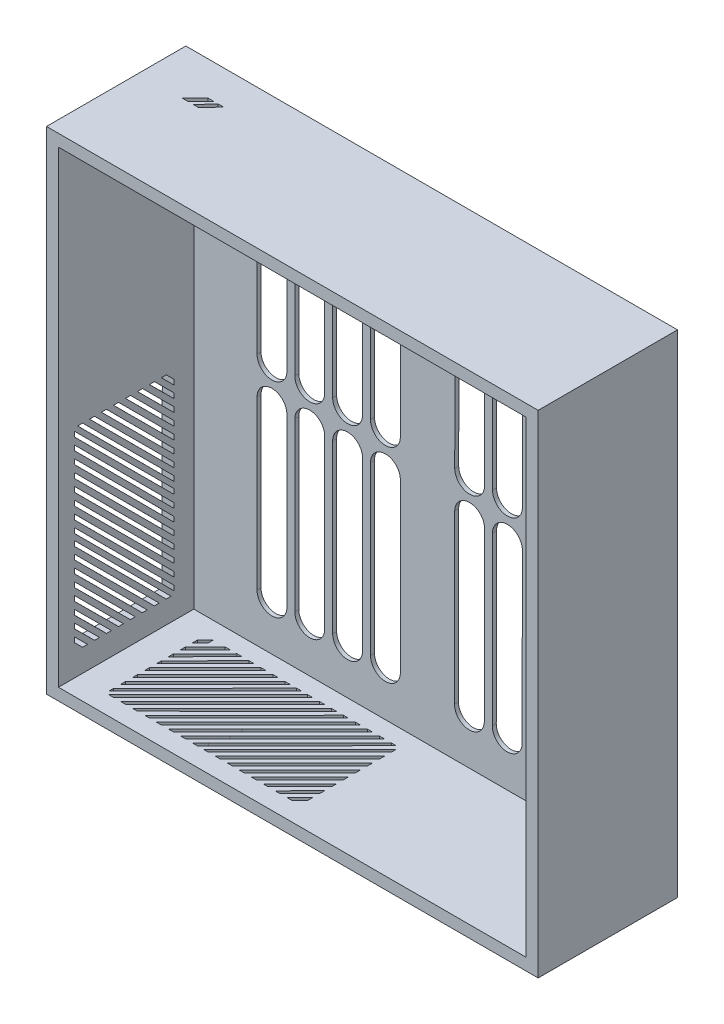
SolidWorks part; units mm, degrees
ref_plane "Plano frontal" through (0, 0, 0) normal (0, 0, 1) x (1, 0, 0)
ref_plane "Plano superior" through (0, 0, 0) normal (0, 1, 0) x (1, 0, 0)
ref_plane "Plano direito" through (0, 0, 0) normal (1, 0, 0) x (0, 0, -1)
sketch "Esboço1" plane through (0, 0, 0) normal (0, 0, 1) x (1, 0, 0)
  line L1 (-16.5696, 236.8339) -> (230.4304, 236.8339)
  line L2 (-16.5696, 236.8339) -> (-16.5696, -10.1661)
  line L3 (-16.5696, -10.1661) -> (230.4304, -10.1661)
  line L4 (230.4304, 236.8339) -> (230.4304, -10.1661)
  dimension "D1" = 247
  dimension "D2" = 247
extrude "Ressalto-extrusão1" add sketch "Esboço1" along normal blind 70 contours L2 L1 L4 L3
sketch "Esboço2" plane through (0, 0, 70) normal (0, 0, 1) x (1, 0, 0)
  line L0 (230.4304, 236.8339) -> (230.4304, -10.1661) construction
  line L1 (-10.5696, 230.8339) -> (224.4304, 230.8339)
  line L2 (-10.5696, 230.8339) -> (-10.5696, -4.1661)
  line L3 (-10.5696, -4.1661) -> (224.4304, -4.1661)
  line L4 (224.4304, 230.8339) -> (224.4304, -4.1661)
  line L5 (-16.5696, 236.8339) -> (230.4304, 236.8339) construction
  line L6 (-16.5696, 236.8339) -> (-16.5696, -10.1661) construction
  line L7 (-16.5696, -10.1661) -> (230.4304, -10.1661) construction
  dimension "D1" = 6
  dimension "D2" = 6
  dimension "D3" = 6
  dimension "D4" = 6
extrude "Corte-extrusão1" cut sketch "Esboço2" against normal blind 68
sketch "Esboço6" plane through (0, 0, 2) normal (0, 0, 1) x (1, 0, 0)
  line L0 (21.1965, 206.6676) -> (21.1965, 122.654)
  line L1 (36.1965, 206.6676) -> (36.1965, 122.654)
  line L2 (40.1965, 206.6676) -> (40.1965, 122.654)
  line L3 (55.1965, 122.654) -> (55.1965, 206.6676)
  line L4 (59.1965, 206.6676) -> (59.1965, 122.654)
  line L5 (78.1965, 206.6676) -> (78.1965, 122.654)
  line L6 (74.1965, 122.654) -> (74.1965, 206.6676)
  line L7 (93.1965, 122.654) -> (93.1965, 206.6676)
  line L9 (93.1965, 104.0138) -> (93.1965, 20.0002)
  line L17 (-10.5696, 113.3339) -> (224.4304, 113.3339) construction
  line L18 (-10.5696, 230.8339) -> (-10.5696, -4.1661) construction
  line L19 (224.4304, -4.1661) -> (224.4304, 230.8339) construction
  line L20 (74.1965, 104.0138) -> (74.1965, 20.0002)
  line L21 (78.1965, 20.0002) -> (78.1965, 104.0138)
  line L22 (59.1965, 20.0002) -> (59.1965, 104.0138)
  line L23 (55.1965, 104.0138) -> (55.1965, 20.0002)
  line L24 (40.1965, 20.0002) -> (40.1965, 104.0138)
  line L25 (36.1965, 20.0002) -> (36.1965, 104.0138)
  line L26 (21.1965, 20.0002) -> (21.1965, 104.0138)
  line L27 (192.3761, 19.8832) -> (192.4909, 103.8967)
  line L28 (106.9201, 215.6583) -> (106.9304, 230.8339) construction
  line L29 (224.4304, 230.8339) -> (-10.5696, 230.8339) construction
  line L30 (177.3761, 19.9037) -> (177.4909, 103.9172)
  line L31 (173.3761, 19.9092) -> (173.491, 103.9227)
  line L32 (158.491, 103.9432) -> (158.3762, 19.9297)
  line L33 (154.3762, 19.9351) -> (154.491, 103.9487)
  line L34 (135.3762, 19.9611) -> (135.491, 103.9746)
  line L35 (139.491, 103.9692) -> (139.3762, 19.9556)
  line L36 (120.491, 103.9951) -> (120.3762, 19.9816)
  line L37 (120.5165, 122.6353) -> (120.6313, 206.6489)
  line L38 (139.5165, 122.6094) -> (139.6313, 206.6229)
  line L39 (135.6313, 206.6284) -> (135.5165, 122.6148)
  line L40 (154.6313, 206.6024) -> (154.5164, 122.5889)
  line L41 (158.5164, 122.5834) -> (158.6312, 206.5969)
  line L42 (173.6312, 206.5764) -> (173.5164, 122.5629)
  line L43 (177.6312, 206.571) -> (177.5164, 122.5574)
  line L44 (192.6312, 206.5505) -> (192.5164, 122.5369)
  line L45 (-10.5696, -4.1661) -> (224.4304, -4.1661) construction
  arc A112 (36.1965, 206.6676) -> (21.1965, 206.6676) centre (28.6965, 206.6676) ccw
  arc A113 (21.1965, 122.654) -> (36.1965, 122.654) centre (28.6965, 122.654) ccw
  arc A114 (40.1965, 206.6676) -> (55.1965, 206.6676) centre (47.6965, 206.6676) cw
  arc A115 (40.1965, 122.654) -> (55.1965, 122.654) centre (47.6965, 122.654) ccw
  arc A116 (59.1965, 206.6676) -> (74.1965, 206.6676) centre (66.6965, 206.6676) cw
  arc A117 (59.1965, 122.654) -> (74.1965, 122.654) centre (66.6965, 122.654) ccw
  arc A118 (78.1965, 206.6676) -> (93.1965, 206.6676) centre (85.6965, 206.6676) cw
  arc A119 (78.1965, 122.654) -> (93.1965, 122.654) centre (85.6965, 122.654) ccw
  arc A128 (78.1965, 104.0138) -> (93.1965, 104.0138) centre (85.6965, 104.0138) cw
  arc A129 (78.1965, 20.0002) -> (93.1965, 20.0002) centre (85.6965, 20.0002) ccw
  arc A130 (59.1965, 104.0138) -> (74.1965, 104.0138) centre (66.6965, 104.0138) cw
  arc A131 (59.1965, 20.0002) -> (74.1965, 20.0002) centre (66.6965, 20.0002) ccw
  arc A132 (40.1965, 104.0138) -> (55.1965, 104.0138) centre (47.6965, 104.0138) cw
  arc A133 (40.1965, 20.0002) -> (55.1965, 20.0002) centre (47.6965, 20.0002) ccw
  arc A134 (21.1965, 104.0138) -> (36.1965, 104.0138) centre (28.6965, 104.0138) cw
  arc A135 (36.1965, 20.0002) -> (21.1965, 20.0002) centre (28.6965, 20.0002) cw
  arc A136 (177.3761, 19.9037) -> (192.3761, 19.8832) centre (184.8761, 19.8935) ccw
  arc A137 (192.4909, 103.8967) -> (177.4909, 103.9172) centre (184.9909, 103.907) ccw
  arc A138 (173.3761, 19.9092) -> (158.3762, 19.9297) centre (165.8762, 19.9194) cw
  arc A139 (173.491, 103.9227) -> (158.491, 103.9432) centre (165.991, 103.933) ccw
  arc A140 (154.3762, 19.9351) -> (139.3762, 19.9556) centre (146.8762, 19.9454) cw
  arc A141 (154.491, 103.9487) -> (139.491, 103.9692) centre (146.991, 103.9589) ccw
  arc A142 (135.3762, 19.9611) -> (120.3762, 19.9816) centre (127.8762, 19.9713) cw
  arc A143 (135.491, 103.9746) -> (120.491, 103.9951) centre (127.991, 103.9849) ccw
  arc A144 (135.5165, 122.6148) -> (120.5165, 122.6353) centre (128.0165, 122.6251) cw
  arc A145 (135.6313, 206.6284) -> (120.6313, 206.6489) centre (128.1313, 206.6386) ccw
  arc A146 (154.5164, 122.5889) -> (139.5165, 122.6094) centre (147.0165, 122.5991) cw
  arc A147 (154.6313, 206.6024) -> (139.6313, 206.6229) centre (147.1313, 206.6127) ccw
  arc A148 (173.5164, 122.5629) -> (158.5164, 122.5834) centre (166.0164, 122.5731) cw
  arc A149 (173.6312, 206.5764) -> (158.6312, 206.5969) centre (166.1312, 206.5867) ccw
  arc A150 (192.5164, 122.5369) -> (177.5164, 122.5574) centre (185.0164, 122.5472) cw
  arc A151 (177.6312, 206.571) -> (192.6312, 206.5505) centre (185.1312, 206.5607) cw
  dimension "D1" = 19
  dimension "D2" = 19
  dimension "D3" = 19
  dimension "D4" = 19
  dimension "D14" = 7.5
  dimension "D15" = 7.5
  dimension "D16" = 7.5
  dimension "D17" = 7.5
  dimension "D5" = 19
  dimension "D6" = 19
  dimension "D7" = 19
  dimension "D8" = 19
  dimension "D9" = 18.9745
  dimension "D10" = 19
  dimension "D11" = 19
  dimension "D12" = 19
  dimension "D13" = 21.2174
extrude "Corte-extrusão2" cut sketch "Esboço6" against normal through all
sketch "Esboço8" plane through (-16.5696, 0, 0) normal (-1, 0, 0) x (0, 0, 1)
  line L7 (11.8956, 54.7334) -> (61.8956, 54.7334) construction
  line L11 (61.8956, 7.1713) -> (61.8956, 104.6924) construction
  line L12 (61.8956, 104.6924) -> (11.8956, 104.6924) construction
  line L13 (11.8956, 104.6924) -> (11.8956, 7.1713) construction
  line L169 (11.8956, 100.7307) -> (15.8573, 104.6924)
  line L170 (11.8956, 98.2307) -> (18.3573, 104.6924)
  line L171 (18.3573, 104.6924) -> (15.8573, 104.6924)
  line L172 (11.8956, 98.2307) -> (11.8956, 100.7307)
  line L173 (11.8523, 94.7756) -> (21.7577, 104.6924)
  line L174 (11.8538, 92.2756) -> (24.3573, 104.6924)
  line L175 (24.3573, 104.6924) -> (21.7577, 104.6924)
  line L176 (11.8538, 92.2756) -> (11.8523, 94.7756)
  line L177 (11.8619, 88.7609) -> (27.7906, 104.6924)
  line L178 (11.8622, 86.2609) -> (30.3573, 104.6924)
  line L179 (30.3573, 104.6924) -> (27.7906, 104.6924)
  line L180 (11.8622, 86.2609) -> (11.8619, 88.7609)
  line L181 (11.8641, 82.7649) -> (33.7943, 104.6924)
  line L182 (11.8639, 80.2649) -> (36.3573, 104.6924)
  line L183 (36.3573, 104.6924) -> (33.7943, 104.6924)
  line L184 (11.8639, 80.2649) -> (11.8641, 82.7649)
  line L185 (11.8656, 76.7627) -> (39.8121, 104.6924)
  line L186 (11.8648, 74.2627) -> (42.3573, 104.6924)
  line L187 (42.3573, 104.6924) -> (39.8121, 104.6924)
  line L188 (11.8648, 74.2627) -> (11.8656, 76.7627)
  line L189 (11.9387, 70.7309) -> (45.8573, 104.6924)
  line L190 (11.9387, 68.2309) -> (48.4001, 104.6924)
  line L191 (48.4001, 104.6924) -> (45.8573, 104.6924)
  line L192 (11.9387, 68.2309) -> (11.9387, 70.7309)
  line L193 (11.8959, 64.7311) -> (51.9039, 104.6924)
  line L194 (11.8959, 62.2311) -> (54.4071, 104.6924)
  line L195 (54.4071, 104.6924) -> (51.9039, 104.6924)
  line L196 (11.8959, 62.2311) -> (11.8959, 64.7311)
  line L197 (11.8715, 58.7626) -> (57.8573, 104.6924)
  line L198 (11.87, 56.2626) -> (60.3573, 104.6924)
  line L199 (60.3573, 104.6924) -> (57.8573, 104.6924)
  line L200 (11.87, 56.2626) -> (11.8715, 58.7626)
  line L201 (61.4363, 104.2154) -> (11.8956, 54.7334) construction
  line L202 (61.912, 103.1358) -> (61.909, 100.6358)
  line L203 (13.4247, 54.706) -> (61.912, 103.1358)
  line L204 (15.9247, 54.7033) -> (61.909, 100.6358)
  line L205 (61.9049, 97.1857) -> (61.902, 94.6825)
  line L206 (61.8978, 91.1787) -> (61.8948, 88.6358)
  line L207 (61.8906, 85.1358) -> (61.8876, 82.5906)
  line L208 (61.8835, 79.1358) -> (61.8805, 76.5729)
  line L209 (61.8764, 73.1358) -> (61.8734, 70.5692)
  line L210 (61.8693, 67.1359) -> (61.8662, 64.5363)
  line L211 (61.8622, 61.1359) -> (61.8592, 58.6359)
  line L212 (60.3408, 57.1191) -> (61.8592, 58.6359)
  line L213 (57.8332, 57.1218) -> (61.8622, 61.1359)
  line L214 (59.4625, 54.7334) -> (11.8956, 54.7334) construction
  line L215 (51.9262, 57.1282) -> (61.8693, 67.1359)
  line L216 (11.9387, 47.12) -> (21.9593, 57.1605)
  line L217 (11.936, 44.62) -> (24.4519, 57.1578)
  line L218 (11.936, 44.62) -> (11.9387, 47.12)
  line L219 (11.9322, 41.1181) -> (27.8522, 57.1541)
  line L220 (11.9295, 38.6181) -> (30.391, 57.1514)
  line L221 (11.9295, 38.6181) -> (11.9322, 41.1181)
  line L222 (11.9258, 35.1164) -> (33.8937, 57.1476)
  line L223 (11.9231, 32.6463) -> (36.4316, 57.1449)
  line L224 (11.9231, 32.6463) -> (11.9258, 35.1164)
  line L225 (11.9193, 29.1152) -> (39.8992, 57.1411)
  line L226 (11.9166, 26.6516) -> (42.4294, 57.1384)
  line L227 (11.9166, 26.6516) -> (11.9193, 29.1152)
  line L228 (11.9128, 23.1198) -> (45.8987, 57.1347)
  line L229 (11.9102, 20.6616) -> (48.4211, 57.1319)
  line L230 (11.9102, 20.6616) -> (11.9128, 23.1198)
  line L231 (11.9064, 17.1283) -> (51.9262, 57.1282)
  line L232 (11.9037, 14.6719) -> (54.4408, 57.1254)
  line L233 (11.9037, 14.6719) -> (11.9064, 17.1283)
  line L234 (11.897, 11.1632) -> (57.8332, 57.1218)
  line L235 (11.8973, 8.7278) -> (60.3408, 57.1191)
  line L236 (11.8973, 8.7278) -> (11.897, 11.1632)
  line L237 (59.0348, 54.2596) -> (11.8956, 7.1713) construction
  line L238 (13.4521, 7.1713) -> (15.8875, 7.1684)
  line L239 (61.8956, 55.5626) -> (61.8956, 53.055)
  line L240 (13.4521, 7.1713) -> (61.8956, 55.5626)
  line L241 (15.8875, 7.1684) -> (61.8956, 53.055)
  line L242 (19.3962, 7.1713) -> (21.8526, 7.1713)
  line L243 (61.8956, 49.6626) -> (61.8956, 47.1479)
  line L244 (19.3962, 7.1713) -> (61.8956, 49.6626)
  line L245 (21.8526, 7.1713) -> (61.8956, 47.1479)
  line L246 (25.3859, 7.1713) -> (27.8441, 7.1713)
  line L247 (61.8956, 43.6429) -> (61.8956, 41.1204)
  line L248 (25.3859, 7.1713) -> (61.8956, 43.6429)
  line L249 (27.8441, 7.1713) -> (61.8956, 41.1204)
  line L250 (31.3759, 7.1713) -> (33.8396, 7.1713)
  line L251 (61.8956, 37.6512) -> (61.8956, 35.121)
  line L252 (31.3759, 7.1713) -> (61.8956, 37.6512)
  line L253 (33.8396, 7.1713) -> (61.8956, 35.121)
  line L254 (37.3706, 7.1713) -> (39.8407, 7.1713)
  line L255 (61.8956, 31.6534) -> (61.8956, 29.1154)
  line L256 (37.3706, 7.1713) -> (61.8956, 31.6534)
  line L257 (39.8407, 7.1713) -> (61.8956, 29.1154)
  line L258 (43.3424, 7.1713) -> (45.8424, 7.1713)
  line L259 (61.8956, 25.6127) -> (61.8956, 23.074)
  line L260 (43.3424, 7.1713) -> (61.8956, 25.6127)
  line L261 (45.8424, 7.1713) -> (61.8956, 23.074)
  line L262 (49.3443, 7.1713) -> (51.8443, 7.1713)
  line L263 (61.8956, 19.6736) -> (61.8956, 17.181)
  line L264 (49.3443, 7.1713) -> (61.8956, 19.6736)
  line L265 (51.8443, 7.1713) -> (61.8956, 17.181)
  line L266 (55.3872, 7.1713) -> (57.8872, 7.1713)
  line L267 (61.906, 13.6631) -> (61.8956, 11.1631)
  line L268 (55.3872, 7.1713) -> (61.906, 13.6631)
  line L269 (57.8872, 7.1713) -> (61.8956, 11.1631)
  line L270 (13.4247, 54.706) -> (11.8956, 53.1787)
  line L271 (11.8956, 53.1787) -> (11.8956, 50.6787)
  line L272 (11.8956, 50.6787) -> (15.9247, 54.7033)
  line L273 (21.9593, 57.1605) -> (61.9049, 97.1857)
  line L274 (24.4519, 57.1578) -> (61.902, 94.6825)
  line L275 (27.8522, 57.1541) -> (61.8978, 91.1787)
  line L276 (30.391, 57.1514) -> (61.8948, 88.6358)
  line L277 (13.4521, 7.1713) -> (61.8956, 7.1713) construction
  line L278 (54.4408, 57.1254) -> (61.8662, 64.5363)
  line L279 (45.8987, 57.1347) -> (61.8764, 73.1358)
  line L280 (48.4211, 57.1319) -> (61.8734, 70.5692)
  line L281 (39.8992, 57.1411) -> (61.8835, 79.1358)
  line L282 (42.4294, 57.1384) -> (61.8805, 76.5729)
  line L283 (33.8937, 57.1476) -> (61.8906, 85.1358)
  line L284 (36.4316, 57.1449) -> (61.8876, 82.5906)
extrude "Corte-extrusão4" cut sketch "Esboço8" against normal blind 13
sketch "Esboço12" plane through (0, -10.1661, 0) normal (0, -1, 0) x (1, 0, 0)
  line L0 (51.3426, 60.5914) -> (51.3426, 10.5914) construction
  line L1 (3.7805, 10.5914) -> (101.3015, 10.5914) construction
  line L2 (101.3015, 10.5914) -> (101.3015, 60.5914) construction
  line L3 (101.3015, 60.5914) -> (3.7805, 60.5914) construction
  line L4 (97.3399, 60.5914) -> (101.3015, 56.6298)
  line L5 (94.8399, 60.5914) -> (101.3015, 54.1298)
  line L6 (101.3015, 54.1298) -> (101.3015, 56.6298)
  line L7 (94.8399, 60.5914) -> (97.3399, 60.5914)
  line L8 (91.3847, 60.6347) -> (101.3015, 50.7294)
  line L9 (88.8847, 60.6333) -> (101.3015, 48.1298)
  line L10 (101.3015, 48.1298) -> (101.3015, 50.7294)
  line L11 (88.8847, 60.6333) -> (91.3847, 60.6347)
  line L12 (85.37, 60.6251) -> (101.3015, 44.6965)
  line L13 (82.87, 60.6249) -> (101.3015, 42.1298)
  line L14 (101.3015, 42.1298) -> (101.3015, 44.6965)
  line L15 (82.87, 60.6249) -> (85.37, 60.6251)
  line L16 (79.3741, 60.623) -> (101.3015, 38.6927)
  line L17 (76.8741, 60.6231) -> (101.3015, 36.1298)
  line L18 (101.3015, 36.1298) -> (101.3015, 38.6927)
  line L19 (76.8741, 60.6231) -> (79.3741, 60.623)
  line L20 (73.3718, 60.6215) -> (101.3015, 32.675)
  line L21 (70.8718, 60.6222) -> (101.3015, 30.1298)
  line L22 (101.3015, 30.1298) -> (101.3015, 32.675)
  line L23 (70.8718, 60.6222) -> (73.3718, 60.6215)
  line L24 (67.3401, 60.5484) -> (101.3015, 26.6298)
  line L25 (64.8401, 60.5484) -> (101.3015, 24.0869)
  line L26 (101.3015, 24.0869) -> (101.3015, 26.6298)
  line L27 (64.8401, 60.5484) -> (67.3401, 60.5484)
  line L28 (61.3402, 60.5911) -> (101.3015, 20.5832)
  line L29 (58.8402, 60.5911) -> (101.3015, 18.0799)
  line L30 (101.3015, 18.0799) -> (101.3015, 20.5832)
  line L31 (58.8402, 60.5911) -> (61.3402, 60.5911)
  line L32 (55.3717, 60.6155) -> (101.3015, 14.6298)
  line L33 (52.8717, 60.617) -> (101.3015, 12.1298)
  line L34 (101.3015, 12.1298) -> (101.3015, 14.6298)
  line L35 (52.8717, 60.617) -> (55.3717, 60.6155)
  line L36 (100.8245, 11.0508) -> (51.3426, 60.5914) construction
  line L37 (99.745, 10.5751) -> (97.245, 10.578)
  line L38 (51.3152, 59.0623) -> (99.745, 10.5751)
  line L39 (51.3124, 56.5623) -> (97.245, 10.578)
  line L40 (93.7949, 10.5821) -> (91.2916, 10.5851)
  line L41 (87.7879, 10.5893) -> (85.245, 10.5923)
  line L42 (81.745, 10.5964) -> (79.1998, 10.5994)
  line L43 (75.745, 10.6035) -> (73.1821, 10.6066)
  line L44 (69.745, 10.6106) -> (67.1783, 10.6137)
  line L45 (63.745, 10.6177) -> (61.1454, 10.6208)
  line L46 (57.745, 10.6248) -> (55.245, 10.6278)
  line L47 (53.7282, 12.1462) -> (55.245, 10.6278)
  line L48 (53.7309, 14.6538) -> (57.745, 10.6248)
  line L49 (51.3426, 13.0246) -> (51.3426, 60.5914) construction
  line L50 (53.7373, 20.5609) -> (63.745, 10.6177)
  line L51 (43.7291, 60.5483) -> (53.7696, 50.5278)
  line L52 (41.2291, 60.551) -> (53.7669, 48.0352)
  line L53 (41.2291, 60.551) -> (43.7291, 60.5483)
  line L54 (37.7272, 60.5548) -> (53.7633, 44.6348)
  line L55 (35.2272, 60.5575) -> (53.7605, 42.0961)
  line L56 (35.2272, 60.5575) -> (37.7272, 60.5548)
  line L57 (31.7256, 60.5613) -> (53.7567, 38.5934)
  line L58 (29.2554, 60.5639) -> (53.754, 36.0555)
  line L59 (29.2554, 60.5639) -> (31.7256, 60.5613)
  line L60 (25.7244, 60.5678) -> (53.7503, 32.5878)
  line L61 (23.2608, 60.5704) -> (53.7475, 30.0577)
  line L62 (23.2608, 60.5704) -> (25.7244, 60.5678)
  line L63 (19.7289, 60.5742) -> (53.7438, 26.5884)
  line L64 (17.2708, 60.5769) -> (53.7411, 24.0659)
  line L65 (17.2708, 60.5769) -> (19.7289, 60.5742)
  line L66 (13.7374, 60.5807) -> (53.7373, 20.5609)
  line L67 (11.2811, 60.5833) -> (53.7346, 18.0463)
  line L68 (11.2811, 60.5833) -> (13.7374, 60.5807)
  line L69 (7.7723, 60.5901) -> (53.7309, 14.6538)
  line L70 (5.3369, 60.5898) -> (53.7282, 12.1462)
  line L71 (5.3369, 60.5898) -> (7.7723, 60.5901)
  line L72 (50.8688, 13.4523) -> (3.7805, 60.5914) construction
  line L73 (3.7805, 59.035) -> (3.7775, 56.5996)
  line L74 (52.1717, 10.5914) -> (49.6641, 10.5914)
  line L75 (3.7805, 59.035) -> (52.1717, 10.5914)
  line L76 (3.7775, 56.5996) -> (49.6641, 10.5914)
  line L77 (3.7805, 53.0908) -> (3.7805, 50.6345)
  line L78 (46.2717, 10.5914) -> (43.7571, 10.5914)
  line L79 (3.7805, 53.0908) -> (46.2717, 10.5914)
  line L80 (3.7805, 50.6345) -> (43.7571, 10.5914)
  line L81 (3.7805, 47.1011) -> (3.7805, 44.643)
  line L82 (40.2521, 10.5914) -> (37.7296, 10.5914)
  line L83 (3.7805, 47.1011) -> (40.2521, 10.5914)
  line L84 (3.7805, 44.643) -> (37.7296, 10.5914)
  line L85 (3.7805, 41.1111) -> (3.7805, 38.6475)
  line L86 (34.2603, 10.5914) -> (31.7301, 10.5914)
  line L87 (3.7805, 41.1111) -> (34.2603, 10.5914)
  line L88 (3.7805, 38.6475) -> (31.7301, 10.5914)
  line L89 (3.7805, 35.1165) -> (3.7805, 32.6463)
  line L90 (28.2625, 10.5914) -> (25.7246, 10.5914)
  line L91 (3.7805, 35.1165) -> (28.2625, 10.5914)
  line L92 (3.7805, 32.6463) -> (25.7246, 10.5914)
  line L93 (3.7805, 29.1446) -> (3.7805, 26.6446)
  line L94 (22.2219, 10.5914) -> (19.6831, 10.5914)
  line L95 (3.7805, 29.1446) -> (22.2219, 10.5914)
  line L96 (3.7805, 26.6446) -> (19.6831, 10.5914)
  line L97 (3.7805, 23.1428) -> (3.7805, 20.6428)
  line L98 (16.2828, 10.5914) -> (13.7902, 10.5914)
  line L99 (3.7805, 23.1428) -> (16.2828, 10.5914)
  line L100 (3.7805, 20.6428) -> (13.7902, 10.5914)
  line L101 (3.7805, 17.0999) -> (3.7805, 14.5999)
  line L102 (7.7723, 13.0914) -> (7.7723, 10.5914)
  line L103 (3.7805, 17.0999) -> (7.7723, 13.0914)
  line L104 (3.7805, 14.5999) -> (7.7723, 10.5914)
  line L105 (51.3152, 59.0623) -> (49.7878, 60.5914)
  line L106 (49.7878, 60.5914) -> (47.2878, 60.5914)
  line L107 (47.2878, 60.5914) -> (51.3124, 56.5623)
  line L108 (53.7696, 50.5278) -> (93.7949, 10.5821)
  line L109 (53.7669, 48.0352) -> (91.2916, 10.5851)
  line L110 (53.7633, 44.6348) -> (87.7879, 10.5893)
  line L111 (53.7605, 42.0961) -> (85.245, 10.5923)
  line L112 (3.7805, 59.035) -> (3.7805, 10.5914) construction
  line L113 (53.7346, 18.0463) -> (61.1454, 10.6208)
  line L114 (53.7438, 26.5884) -> (69.745, 10.6106)
  line L115 (53.7411, 24.0659) -> (67.1783, 10.6137)
  line L116 (53.7503, 32.5878) -> (75.745, 10.6035)
  line L117 (53.7475, 30.0577) -> (73.1821, 10.6066)
  line L118 (53.7567, 38.5934) -> (81.745, 10.5964)
  line L119 (53.754, 36.0555) -> (79.1998, 10.5994)
  circle A0 centre (200.4856, 24.6567) radius 13.5
  dimension "D1" = 1.1
  dimension "D2" = 1.1
  dimension "D3" = 2.5
  dimension "D4" = 2.5
  dimension "D5" = 2.5
extrude "Corte-extrusão7" cut sketch "Esboço12" against normal blind 10
sketch "Esboço13" plane through (0, 236.8339, 0) normal (0, 1, 0) x (1, 0, 0)
  line L0 (5.2688, -23.5786) -> (11.7536, -17.0938)
  line L1 (11.7536, -17.0938) -> (14.5036, -17.0938)
  line L2 (14.5036, -17.0938) -> (8.0188, -23.5786)
  line L3 (8.0188, -23.5786) -> (5.2688, -23.5786)
  line L4 (10.8022, -23.5786) -> (16.6984, -17.0938)
  line L5 (16.6984, -17.0938) -> (19.4484, -17.0938)
  line L6 (19.4484, -17.0938) -> (13.5522, -23.5786)
  line L7 (13.5522, -23.5786) -> (10.8022, -23.5786)
extrude "Corte-extrusão8" cut sketch "Esboço13" against normal blind 2
sketch "Esboço14" plane through (0, 0, 70) normal (0, 0, 1) x (1, 0, 0)
  line L9 (230.4304, 236.8339) -> (230.4304, -10.1661) construction
  line L11 (-16.5696, 236.8339) -> (230.4304, -10.1661) construction
  line L12 (-16.5696, -10.1661) -> (230.4304, 236.8339) construction
  line L13 (106.9304, 236.8339) -> (106.9304, -10.1661) construction
  line L14 (-16.5696, 236.8339) -> (230.4304, 236.8339) construction
  line L15 (-16.5696, -10.1661) -> (230.4304, -10.1661) construction
  line L16 (106.9304, 113.3339) -> (230.4304, 113.3339) construction
  line L17 (106.9304, 113.3339) -> (-16.5696, 113.3339) construction
  line L18 (-16.5696, 236.8339) -> (-16.5696, -10.1661) construction
